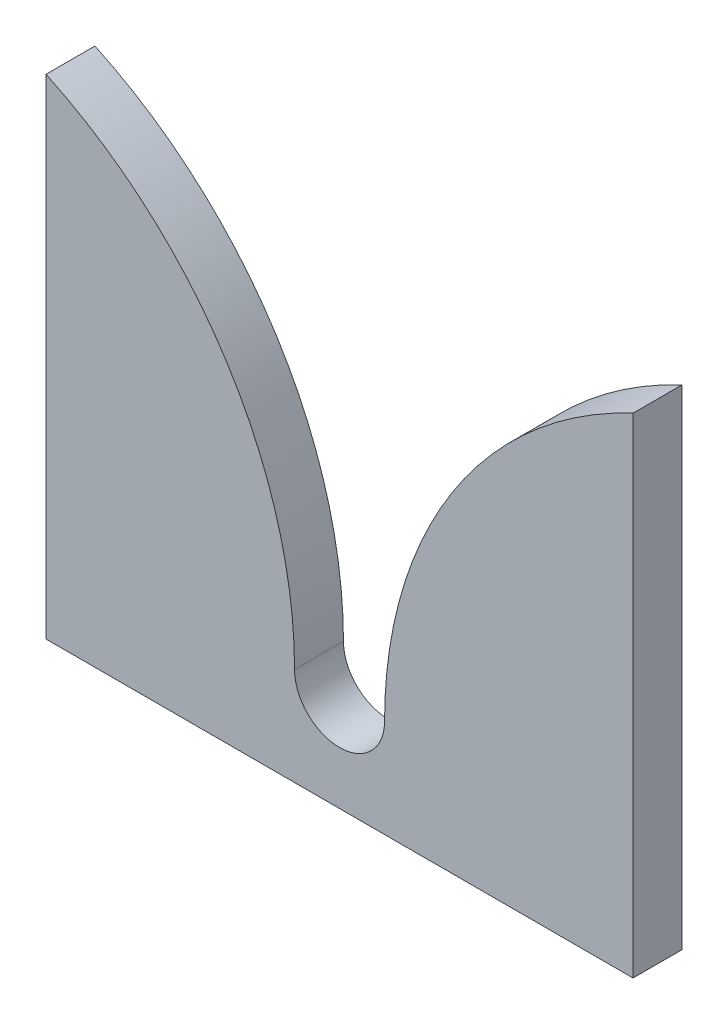
SolidWorks part; units mm, degrees
material "PINE"
ref_plane "Front Plane" through (0, 0, 0) normal (0, 0, 1) x (1, 0, 0)
ref_plane "Top Plane" through (0, 0, 0) normal (0, 1, 0) x (1, 0, 0)
ref_plane "Right Plane" through (0, 0, 0) normal (1, 0, 0) x (0, 0, -1)
sketch "Sketch1" plane through (0, 0, 0) normal (0, 0, 1) x (1, 0, 0)
  line L0 (76.2, 6.35) -> (76.2, 63.5)
  line L1 (0, 0) -> (76.2, 0)
  line L2 (0, 0) -> (0, 6.35)
  line L4 (76.2, 0) -> (76.2, 6.35)
  line L5 (0, 6.35) -> (0, 63.5)
  arc A4 (32.258, 12.7) -> (43.942, 12.7) centre (38.1, 12.7) ccw
  arc A5 (32.258, 12.7) -> (0, 63.5) centre (-23.871, 12.7) ccw
  arc A6 (43.942, 12.7) -> (76.2, 63.5) centre (100.071, 12.7) cw
  dimension "D1" = 56.129
  dimension "D6" = 76.2
  dimension "D2" = 63.5
  dimension "D3" = 12.7
  dimension "D4" = 38.1
extrude "Boss-Extrude2" add sketch "Sketch1" along normal mid plane 6.35
